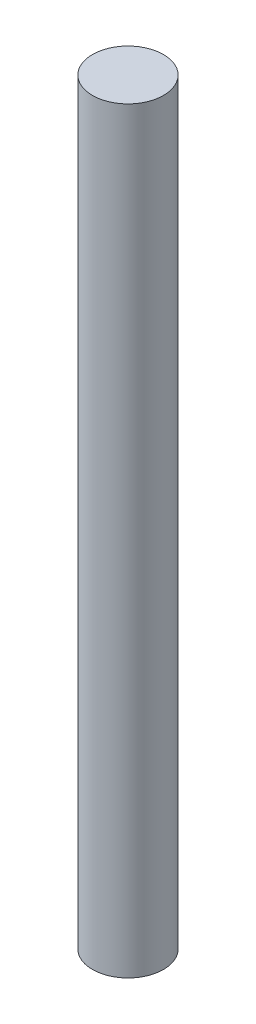
SolidWorks part; units mm, degrees
ref_plane "Plan de face" through (0, 0, 0) normal (0, 0, 1) x (1, 0, 0)
ref_plane "Plan de dessus" through (0, 0, 0) normal (0, 1, 0) x (1, 0, 0)
ref_plane "Plan de droite" through (0, 0, 0) normal (1, 0, 0) x (0, 0, -1)
sketch "Esquisse1" plane through (0, 0, 0) normal (0, 1, 0) x (1, 0, 0)
  circle A0 centre (0, 0) radius 3
  dimension "D1" = 6
extrude "Boss.-Extru.1" add sketch "Esquisse1" along normal blind 64
